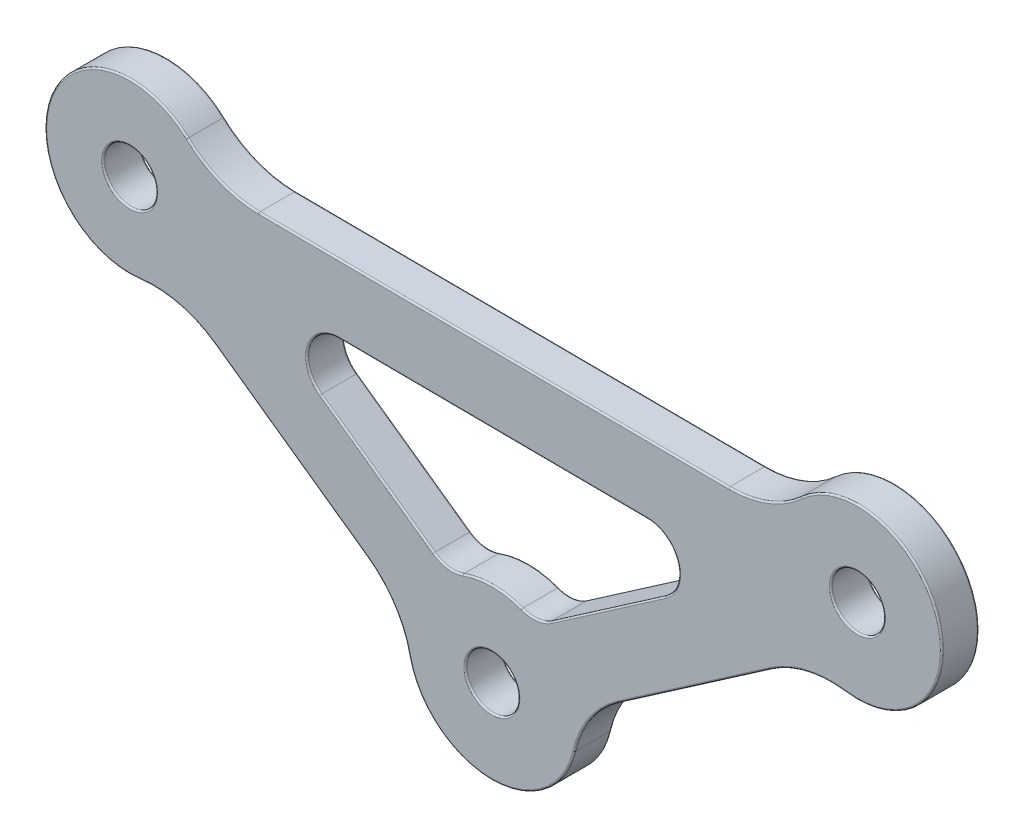
SolidWorks part; units mm, degrees
ref_plane "Front Plane" through (0, 0, 0) normal (0, 0, 1) x (1, 0, 0)
ref_plane "Top Plane" through (0, 0, 0) normal (0, 1, 0) x (1, 0, 0)
ref_plane "Right Plane" through (0, 0, 0) normal (1, 0, 0) x (0, 0, -1)
sketch "Sketch1" plane through (0, 0, 0) normal (0, 0, 1) x (1, 0, 0)
  line L0 (-31.5869, 222.1414) -> (-100.3943, 222.5859) construction
  line L1 (-31.5869, 222.1414) -> (-100.3943, 222.5859) construction
  line L2 (-100.3943, 222.5859) -> (-66.1462, 198.2739) construction
  line L3 (-100.3943, 222.5859) -> (-66.1462, 198.2739) construction
  line L4 (-66.1462, 198.2739) -> (-31.5869, 222.1414) construction
  line L5 (-66.1462, 198.2739) -> (-31.5869, 222.1414) construction
  circle A0 centre (-100.3943, 222.5859) radius 8
  circle A1 centre (-66.1462, 198.2739) radius 8
  circle A2 centre (-31.5869, 222.1414) radius 8
  circle A3 centre (-100.3943, 222.5859) radius 2.5
  circle A4 centre (-66.1462, 198.2739) radius 2.5
  circle A5 centre (-31.5869, 222.1414) radius 2.5
  dimension "D1" = 16
  dimension "D2" = 5
  dimension "D3" = 5
extrude "Boss-Extrude1" add sketch "Sketch1" against normal blind 3.5
sketch "Sketch2" plane through (0, 0, 0) normal (0, 0, 1) x (1, 0, 0)
  line L0 (-93.4906, 222.5413) -> (-38.4906, 222.186)
  line L1 (-31.5869, 222.1414) -> (-100.3943, 222.5859) construction
  line L2 (-95.5017, 219.1128) -> (-71.0388, 201.7471)
  line L3 (-100.3943, 222.5859) -> (-66.1462, 198.2739) construction
  line L4 (-36.524, 218.7317) -> (-61.2092, 201.6836)
  line L5 (-66.1462, 198.2739) -> (-31.5869, 222.1414) construction
  point P12 (-48.8666, 210.2076)
  point P13 (-65.9906, 222.3636)
  point P14 (-83.2703, 210.4299)
  dimension "D1" = 55
  dimension "D2" = 30
extrude "Extrude-Thin1" add sketch "Sketch2" against normal blind 3.5 thin thin type mid plane wall 6.5
fillet "Fillet1" radius 3 4 edges at (-90.1078, 219.2694, -1.75) (-41.9154, 218.958, -1.75) (-70.2258, 205.1556, -1.75) (-61.9781, 205.1023, -1.75)
fillet "Fillet2" radius 10 6 edges at (-73.9884, 199.8553, -1.75) (-58.2843, 199.7538, -1.75) (-38.8759, 225.4385, -1.75) (-35.7551, 215.313, -1.75) (-96.3147, 215.7043, -1.75) (-93.0633, 225.7886, -1.75)
fillet "Fillet3" radius 0.15 46 edges at (-63.6462, 198.2739, -3.5) (-63.6462, 198.2739, 0) (-29.0869, 222.1414, -3.5) (-29.0869, 222.1414, 0) (-97.8943, 222.5859, -3.5) (-97.8943, 222.5859, 0) (-40.1124, 226.1296, 0) (-40.1124, 226.1296, -3.5) (-65.9696, 225.6136, 0) (-65.9696, 225.6136, -3.5) (-91.818, 226.4636, 0) (-91.818, 226.4636, -3.5) (-108.0083, 225.0408, -3.5) (-108.0083, 225.0408, 0) (-95.6981, 214.4289, 0) (-95.6981, 214.4289, -3.5) (-85.1515, 207.7798, -3.5) (-85.1515, 207.7798, 0) (-75.3957, 200.0166, 0) (-75.3957, 200.0166, -3.5) (-66.1979, 190.2741, 0) (-66.1979, 190.2741, -3.5) (-56.875, 199.897, -3.5) (-56.875, 199.897, 0) (-47.0197, 207.5334, 0) (-47.0197, 207.5334, -3.5) (-36.3881, 214.0458, 0) (-36.3881, 214.0458, -3.5) (-23.9418, 224.4977, -3.5) (-23.9418, 224.4977, 0) (-61.8871, 205.5826, -3.5) (-61.8871, 205.5826, 0) (-66.0946, 206.2738, -3.5) (-66.0946, 206.2738, 0) (-70.3106, 205.6371, 0) (-70.3106, 205.6371, -3.5) (-76.9977, 209.9628, -3.5) (-76.9977, 209.9628, 0) (-83.4679, 217.1285, 0) (-83.4679, 217.1285, -3.5) (-66.0116, 219.1137, 0) (-66.0116, 219.1137, -3.5) (-48.5825, 216.9032, 0) (-48.5825, 216.9032, -3.5) (-55.1447, 209.8216, 0) (-55.1447, 209.8216, -3.5)
